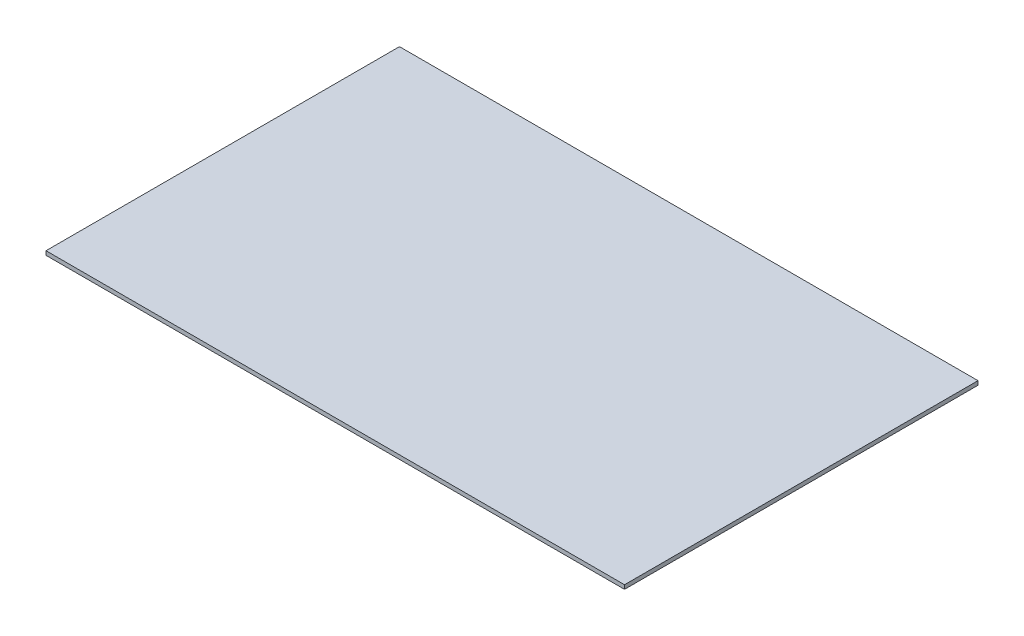
SolidWorks part; units mm, degrees
ref_plane "Front Plane" through (0, 0, 0) normal (0, 0, 1) x (1, 0, 0)
ref_plane "Top Plane" through (0, 0, 0) normal (0, 1, 0) x (1, 0, 0)
ref_plane "Right Plane" through (0, 0, 0) normal (1, 0, 0) x (0, 0, -1)
sketch "Sketch2" plane through (0, 0, 0) normal (0, 1, 0) x (1, 0, 0)
  line L1 (0, 0) -> (1370, 0)
  line L2 (0, 0) -> (0, 837.05)
  line L3 (0, 837.05) -> (1370, 837.05)
  line L4 (1370, 0) -> (1370, 837.05)
  dimension "D1" = 1370
  dimension "D2" = 837.05
extrude "Boss-Extrude1" add sketch "Sketch2" along normal blind 9.525
